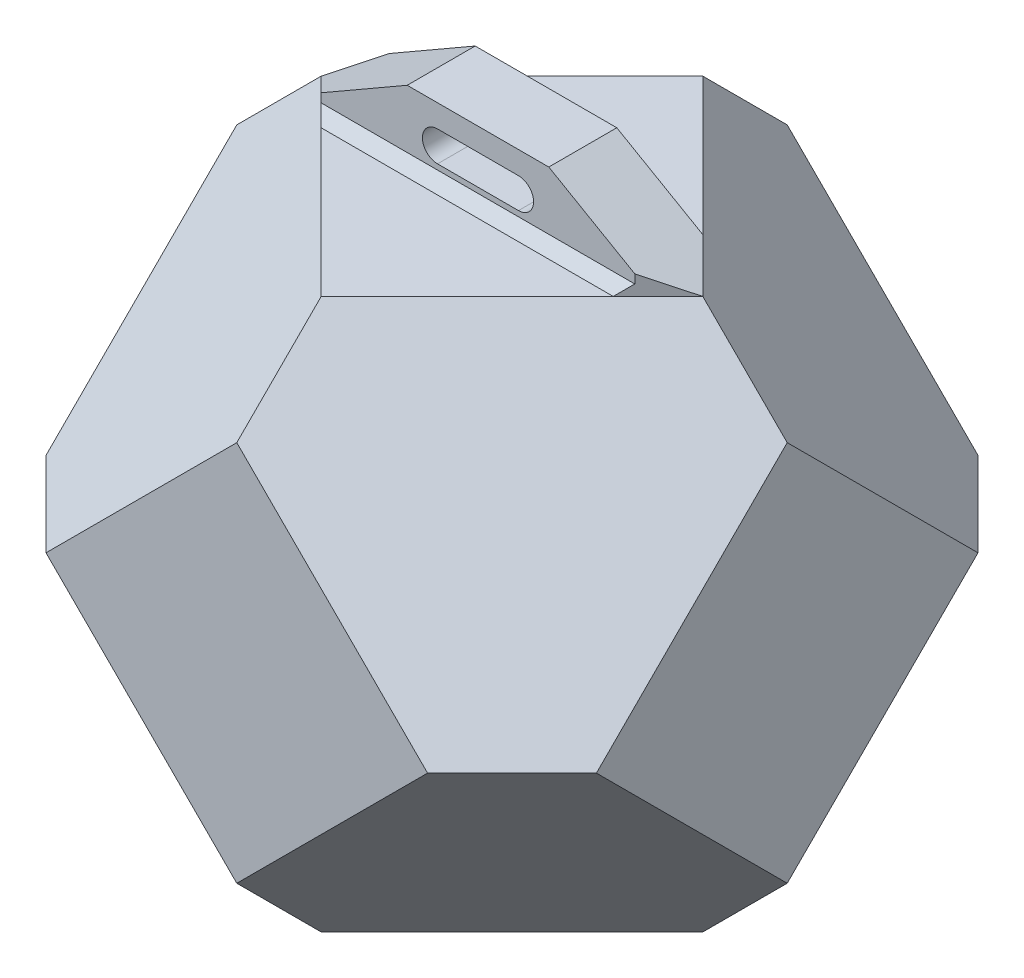
SolidWorks part; units mm, degrees
ref_plane "Front Plane" through (0, 0, 0) normal (0, 0, 1) x (1, 0, 0)
ref_plane "Top Plane" through (0, 0, 0) normal (0, 1, 0) x (1, 0, 0)
ref_plane "Right Plane" through (0, 0, 0) normal (1, 0, 0) x (0, 0, -1)
sketch "Sketch1" plane through (0, 0, 0) normal (0, 1, 0) x (1, 0, 0)
  line L1 (-25.5, 25.5) -> (25.5, 25.5)
  line L2 (-25.5, 25.5) -> (-25.5, -25.5)
  line L3 (-25.5, -25.5) -> (25.5, -25.5)
  line L4 (25.5, 25.5) -> (25.5, -25.5)
  line L5 (-25.5, 25.5) -> (25.5, -25.5) construction
  line L6 (-25.5, -25.5) -> (25.5, 25.5) construction
  point P0 (0, 0)
  dimension "D1" = 51
extrude "Boss-Extrude1" add sketch "Sketch1" along normal mid plane 51
sketch "Sketch2" plane through (0, 25.5, 0) normal (0, 1, 0) x (1, 0, 0)
  line L0 (0, -17.6777) -> (17.6777, 0)
  line L1 (17.6777, 0) -> (0, 17.6777)
  line L2 (0, 17.6777) -> (-17.6777, 0)
  line L3 (-17.6777, 0) -> (0, -17.6777)
  line L4 (0, -17.6777) -> (0, 17.6777) construction
  line L5 (17.6777, 0) -> (-17.6777, 0) construction
  point P2 (0.414, -4.3466)
  dimension "D1" = 25
sketch "Sketch3" plane through (0, 0, -25.5) normal (0, 0, -1) x (-1, 0, 0)
  line L0 (0, 17.6777) -> (-17.6777, 0)
  line L1 (-17.6777, 0) -> (0, -17.6777)
  line L2 (0, -17.6777) -> (17.6777, 0)
  line L3 (17.6777, 0) -> (0, 17.6777)
  line L4 (0, 17.6777) -> (0, -17.6777) construction
  line L5 (-17.6777, 0) -> (17.6777, 0) construction
  dimension "D1" = 25
sketch "Sketch4" plane through (-25.5, 0, 0) normal (-1, 0, 0) x (0, 0, 1)
  line L0 (0, 17.6777) -> (-17.6777, 0)
  line L1 (-17.6777, 0) -> (0, -17.6777)
  line L2 (0, -17.6777) -> (17.6777, 0)
  line L3 (17.6777, 0) -> (0, 17.6777)
  line L4 (0, 17.6777) -> (0, -17.6777) construction
  line L5 (-17.6777, 0) -> (17.6777, 0) construction
  dimension "D1" = 25
sketch3d "3DSketch1"
  line L1 (-25.5, 17.6777, 0) -> (-25.5, 0, -17.6777)
  line L3 (-17.6777, 0, -25.5) -> (0, 17.6777, -25.5)
  line L5 (0, 25.5, -17.6777) -> (-17.6777, 25.5, 0)
  line L6 (-25.5, 17.6777, 0) -> (-25.5, 25.5, 7.8223)
  line L7 (-25.5, 25.5, -25.5) -> (-25.5, 25.5, 25.5) construction
  line L8 (-25.5, 25.5, 7.8223) -> (-17.6777, 25.5, 0)
  line L9 (0, 25.5, -17.6777) -> (7.8223, 25.5, -25.5)
  line L10 (25.5, 25.5, -25.5) -> (-25.5, 25.5, -25.5) construction
  line L11 (7.8223, 25.5, -25.5) -> (0, 17.6777, -25.5)
  line L12 (-17.6777, 0, -25.5) -> (-25.5, -7.8223, -25.5)
  line L13 (-25.5, 25.5, -25.5) -> (-25.5, -25.5, -25.5) construction
  line L14 (-25.5, -7.8223, -25.5) -> (-25.5, 0, -17.6777)
  point P21 (0, 0, 0)
ref_plane "Plane2" through (-14.3926, 14.3926, -14.3926) normal (0.5774, -0.5774, 0.5774) x (0.4082, -0.4082, -0.8165)
extrude "Cut-Extrude2" cut sketch "3DSketch1" along direction (0.5774, -0.5774, 0.5774) on the side of the normal through all
mirror "Mirror1" about plane through (0, 0, 0) normal (0, 1, 0) of "Cut-Extrude2"
mirror "Mirror2" about plane through (0, 0, 0) normal (1, 0, 0) of "Mirror1", "Cut-Extrude2"
mirror "Mirror3" about plane through (0, 0, 0) normal (0, 0, 1) of "Mirror2", "Cut-Extrude2", "Mirror1"
sketch "Sketch6" plane through (0, 25.5, 0) normal (0, 1, 0) x (1, 0, 0)
  line L0 (-17.6777, 0) -> (-14.5277, 3.15)
  line L1 (-17.6777, 0) -> (0, 17.6777) construction
  line L2 (-14.5277, 3.15) -> (14.5277, 3.15)
  line L3 (14.5277, 3.15) -> (17.6777, 0)
  line L4 (17.6777, 0) -> (14.5277, -3.15)
  line L5 (14.5277, -3.15) -> (-14.5277, -3.15)
  line L6 (-14.5277, -3.15) -> (-17.6777, 0)
  line L7 (17.6777, 0) -> (-17.6777, 0) construction
  line L8 (17.6777, 0) -> (0, 17.6777) construction
  line L9 (-17.6777, 0) -> (17.6777, 0) construction
  point P12 (0, 0)
  dimension "D1" = 6.3
extrude "Boss-Extrude2" add sketch "Sketch6" along normal blind 6.4
chamfer "Chamfer3" distance 1 angle 45 2 edges at (0, 25.5, -3.15) (0, 25.5, 3.15)
sketch "Sketch7" plane through (0, 0, 0) normal (0, 0, 1) x (1, 0, 0)
  line L0 (-17.6777, 25.5) -> (-6.56, 31.9)
  line L1 (14.5277, 31.9) -> (-14.5277, 31.9) construction
  line L2 (-6.56, 31.9) -> (-17.6777, 31.9)
  line L3 (-17.6777, 31.9) -> (-17.6777, 25.5)
  line L4 (0, 0) -> (0, 42.4074) construction
  dimension "D1" = 13.12
extrude "Cut-Extrude3" cut sketch "Sketch7" against normal through all both and the other way through all
mirror "Mirror4" about plane through (0, 0, 0) normal (1, 0, 0) of "Cut-Extrude3"
sketch "Sketch8" plane through (0, 0, 0) normal (0, 0, 1) x (1, 0, 0)
  line L0 (-3.75, 28.4) -> (3.75, 28.4) construction
  line L1 (-3.75, 29.8) -> (3.75, 29.8)
  line L2 (-3.75, 27) -> (3.75, 27)
  line L3 (0, -28.05) -> (0, 28.05) construction
  line L4 (17.6777, 25.5) -> (-17.6777, 25.5) construction
  arc A0 (-3.75, 29.8) -> (-3.75, 27) centre (-3.75, 28.4) ccw
  arc A1 (3.75, 27) -> (3.75, 29.8) centre (3.75, 28.4) ccw
  point P2 (0, 28.4)
  point P7 (0, 0)
  dimension "D1" = 2.8
  dimension "D2" = 7.5
  dimension "D3" = 1.5
extrude "Cut-Extrude4" cut sketch "Sketch8" against normal through all both and the other way through all
